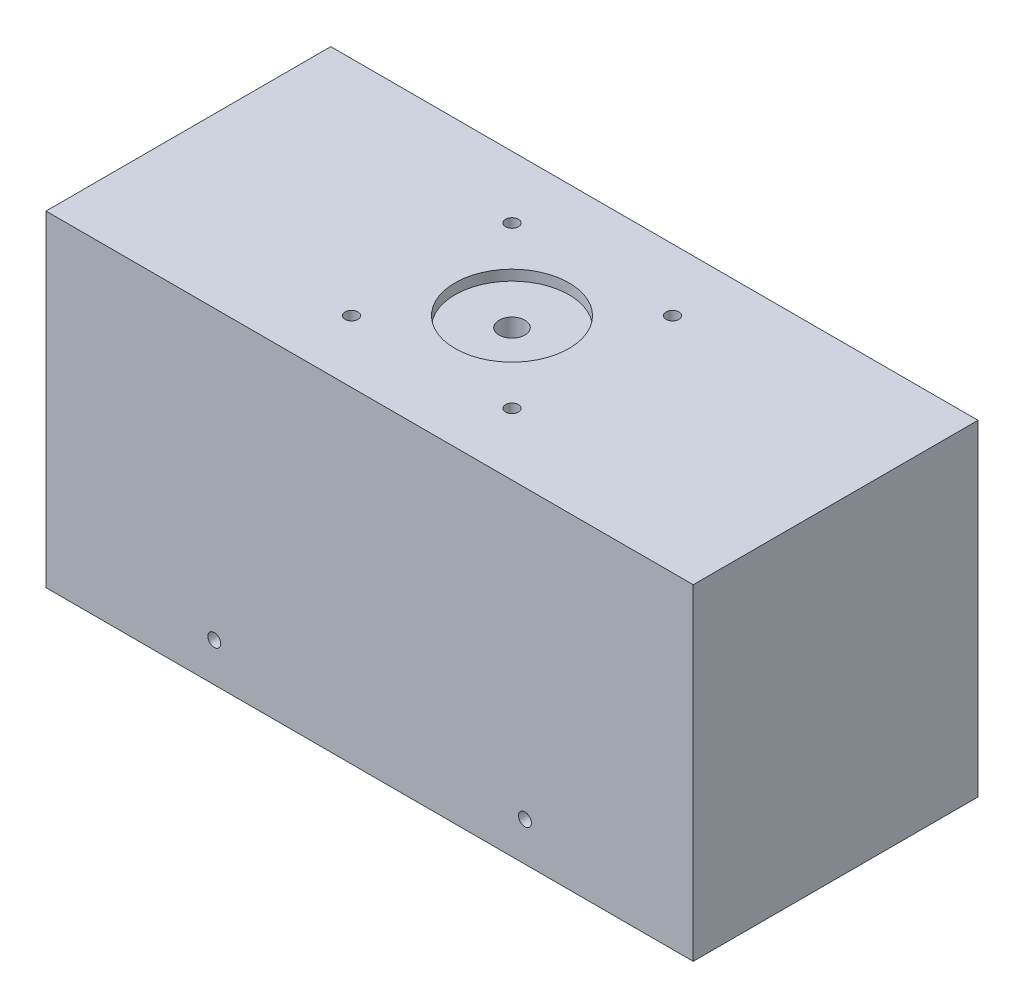
SolidWorks part; units mm, degrees
ref_plane "前视基准面" through (0, 0, 0) normal (0, 0, 1) x (1, 0, 0)
ref_plane "上视基准面" through (0, 0, 0) normal (0, 1, 0) x (1, 0, 0)
ref_plane "右视基准面" through (0, 0, 0) normal (1, 0, 0) x (0, 0, -1)
sketch "草图1" plane through (0, 0, 0) normal (0, 1, 0) x (1, 0, 0)
  line L1 (-62.5, 27.5) -> (62.5, 27.5)
  line L2 (-62.5, 27.5) -> (-62.5, -27.5)
  line L3 (-62.5, -27.5) -> (62.5, -27.5)
  line L4 (62.5, 27.5) -> (62.5, -27.5)
  line L5 (-62.5, 27.5) -> (62.5, -27.5) construction
  line L6 (-62.5, -27.5) -> (62.5, 27.5) construction
  point P0 (0, 0)
  dimension "D1" = 125
  dimension "D2" = 55
extrude "凸台-拉伸1" add sketch "草图1" along normal blind 6
sketch "草图2" plane through (0, 6, 0) normal (0, 1, 0) x (1, 0, 0)
  circle A0 centre (0, 0) radius 11
  dimension "D1" = 22
extrude "切除-拉伸1" cut sketch "草图2" against normal blind 2
sketch "草图3" plane through (0, 4, 0) normal (0, 1, 0) x (1, 0, 0)
  circle A0 centre (0, 0) radius 2.5
  dimension "D1" = 5
extrude "切除-拉伸2" cut sketch "草图3" against normal up to next
hole_wizard "M3 螺纹孔1" positions "草图4" profile "草图5" tap size "M3" standard "GB"
sketch "草图4" plane through (0, 6, 0) normal (0, 1, 0) x (1, 0, 0)
  point P0 (15.5, 15.5)
  point P3 (15.5, -15.5)
  point P6 (-15.5, -15.5)
  point P9 (-15.5, 15.5)
sketch "草图5" plane through (15.5, 6, -15.5) normal (1, 0, 0) x (0, 0, 1)
  line L0 (0, 0) -> (0, 8.2511)
  line L1 (0, 8.2511) -> (1.25, 7.5)
  line L2 (1.25, 7.5) -> (1.25, 0)
  line L5 (1.25, 0) -> (0, 0)
  line L10 (0, 8.2511) -> (-1.25, 7.5) construction
  line L11 (0, -6.35) -> (0, 107.95) construction
  dimension "螺纹孔钻头直径" = 2.5
  dimension "螺纹孔钻头深度" = 7.5
  dimension "导头角度" = 118
cosmetic thread "孔螺蚊线1" parameters "D1"=6, "D2"=3
cosmetic thread "孔螺蚊线2" parameters "D1"=6, "D2"=3
cosmetic thread "孔螺蚊线3" parameters "D1"=6, "D2"=3
cosmetic thread "孔螺蚊线4" parameters "D1"=6, "D2"=3
sketch "草图6" plane through (0, 0, 0) normal (0, -1, 0) x (1, 0, 0)
  line L0 (-62.5, 27.5) -> (62.5, 27.5) construction
  line L1 (60, -25) -> (-60, -25)
  line L2 (60, -25) -> (60, 25)
  line L3 (60, 25) -> (-60, 25)
  line L4 (-60, -25) -> (-60, 25)
  line L5 (60, -25) -> (-60, 25) construction
  line L6 (60, 25) -> (-60, -25) construction
  line L7 (62.5, -27.5) -> (-62.5, -27.5)
  line L8 (62.5, -27.5) -> (62.5, 27.5)
  line L9 (62.5, 27.5) -> (-62.5, 27.5)
  line L10 (-62.5, -27.5) -> (-62.5, 27.5)
  line L11 (62.5, -27.5) -> (-62.5, 27.5) construction
  line L12 (62.5, 27.5) -> (-62.5, -27.5) construction
  point P0 (0, 0)
  point P7 (0, 0)
extrude "凸台-拉伸2" add sketch "草图6" along normal up to vertex (57 mm away)
sketch "草图7" plane through (0, 0, -27.5) normal (0, 0, -1) x (-1, 0, 0)
  line L4 (-62.5, 6) -> (-62.5, -57)
  line L5 (-62.5, -57) -> (62.5, -57)
  line L6 (62.5, -57) -> (62.5, 6)
  line L7 (62.5, 6) -> (-62.5, 6)
  line L8 (-62.5, 6) -> (-62.5, -57)
  line L9 (-62.5, -57) -> (62.5, -57)
  line L10 (62.5, -57) -> (62.5, 6)
  line L11 (62.5, 6) -> (-62.5, 6)
  circle A0 centre (30, -49.5) radius 1.25 construction
  circle A1 centre (-30, -49.5) radius 1.25 construction
  circle A2 centre (30, -49.5) radius 1.25
  circle A3 centre (-30, -49.5) radius 1.25
  dimension "D1" = 0
hole_wizard "M3 螺纹孔2" positions "草图8" profile "草图9" tap size "M3" standard "GB"
sketch "草图8" plane through (0, 0, -27.5) normal (0, 0, -1) x (-1, 0, 0)
  point P0 (30, -49.5)
  point P3 (-30, -49.5)
sketch "草图9" plane through (-30, -49.5, -27.5) normal (1, 0, 0) x (0, 1, 0)
  line L0 (0, 0) -> (0, 2.5)
  line L1 (0, 2.5) -> (1.25, 2.5)
  line L2 (1.25, 2.5) -> (1.25, 0)
  line L5 (1.25, 0) -> (0, 0)
  line L11 (0, -6.35) -> (0, 107.95) construction
  dimension "通孔螺纹孔钻头直径" = 2.5
  dimension "通孔螺纹孔钻头深度" = 2.5
cosmetic thread "孔螺蚊线5" parameters "D2"=3
cosmetic thread "孔螺蚊线6" parameters "D2"=3
hole_wizard "M3 螺纹孔3" positions "草图11" profile "草图12" tap size "M3" standard "GB" end condition up to next
sketch "草图11" plane through (0, 0, 27.5) normal (0, 0, 1) x (1, 0, 0)
  point P0 (30, -49.5)
  point P3 (-30, -49.5)
sketch "草图12" plane through (30, -49.5, 27.5) normal (1, 0, 0) x (0, -1, 0)
  line L0 (0, 0) -> (0, 2.5)
  line L1 (0, 2.5) -> (1.25, 2.5)
  line L2 (1.25, 2.5) -> (1.25, 0)
  line L5 (1.25, 0) -> (0, 0)
  line L11 (0, -6.35) -> (0, 107.95) construction
  dimension "通孔螺纹孔钻头直径" = 2.5
  dimension "通孔螺纹孔钻头深度" = 2.5
cosmetic thread "孔螺蚊线7" parameters "D2"=3
cosmetic thread "孔螺蚊线8" parameters "D2"=3
